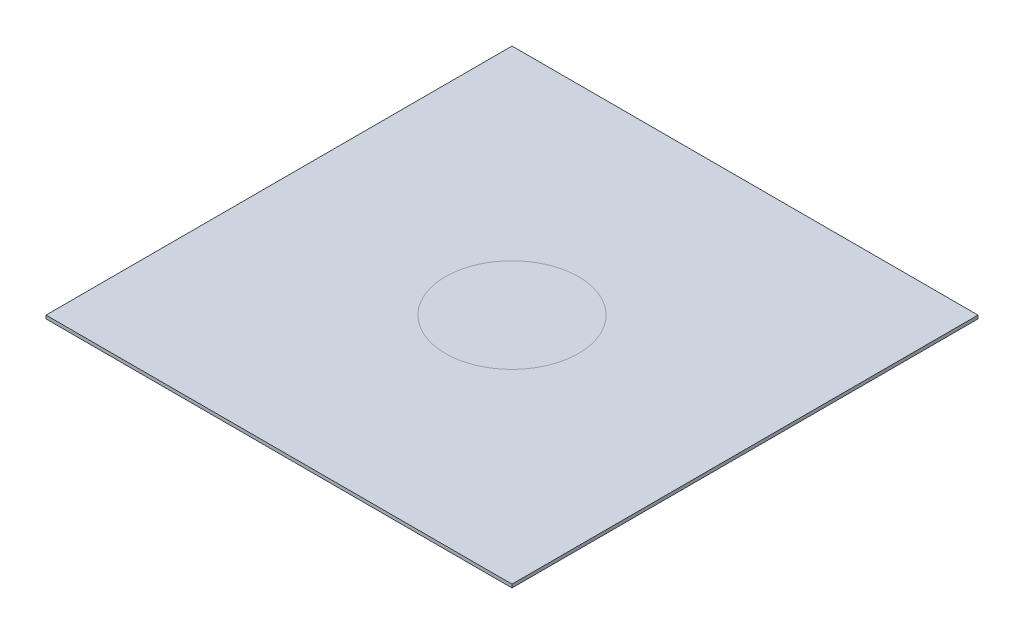
SolidWorks part; units mm, degrees
material "99.5% Aluminum Oxide"
ref_plane "Front Plane" through (0, 0, 0) normal (0, 0, 1) x (1, 0, 0)
ref_plane "Top Plane" through (0, 0, 0) normal (0, 1, 0) x (1, 0, 0)
ref_plane "Right Plane" through (0, 0, 0) normal (1, 0, 0) x (0, 0, -1)
sketch "Sketch1" plane through (0, 0, 0) normal (0, 1, 0) x (1, 0, 0)
  line L1 (-70, -70) -> (70, -70)
  line L2 (-70, -70) -> (-70, 70)
  line L3 (-70, 70) -> (70, 70)
  line L4 (70, -70) -> (70, 70)
  line L5 (-70, -70) -> (70, 70) construction
  line L6 (-70, 70) -> (70, -70) construction
  point P0 (0, 0)
  dimension "D1" = 140
extrude "Boss-Extrude1" add sketch "Sketch1" along normal mid plane 1
sketch "Sketch2" plane through (0, 0.5, 0) normal (0, 1, 0) x (1, 0, 0)
  circle A0 centre (0, 0) radius 20
  dimension "D1" = 40
split line "Split Line1"
equation "\"panel_width\"= 140mm"
equation "\"finger_joint_width\" = 40mm"
equation "\"D1@Sketch1\"=\"panel_width\""
